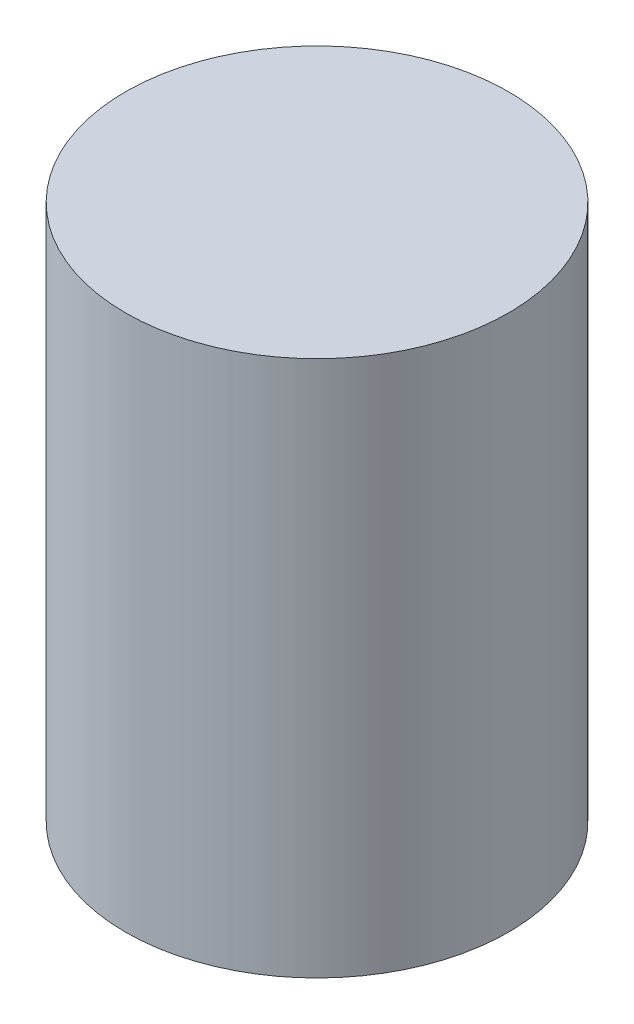
SolidWorks part; units mm, degrees
ref_plane "Front Plane" through (0, 0, 0) normal (0, 0, 1) x (1, 0, 0)
ref_plane "Top Plane" through (0, 0, 0) normal (0, 1, 0) x (1, 0, 0)
ref_plane "Right Plane" through (0, 0, 0) normal (1, 0, 0) x (0, 0, -1)
sketch "Sketch1" plane through (0, 0, 0) normal (0, 1, 0) x (1, 0, 0)
  circle A0 centre (0, 0) radius 25
  dimension "D1" = 50
extrude "Boss-Extrude1" add sketch "Sketch1" along normal blind 70
